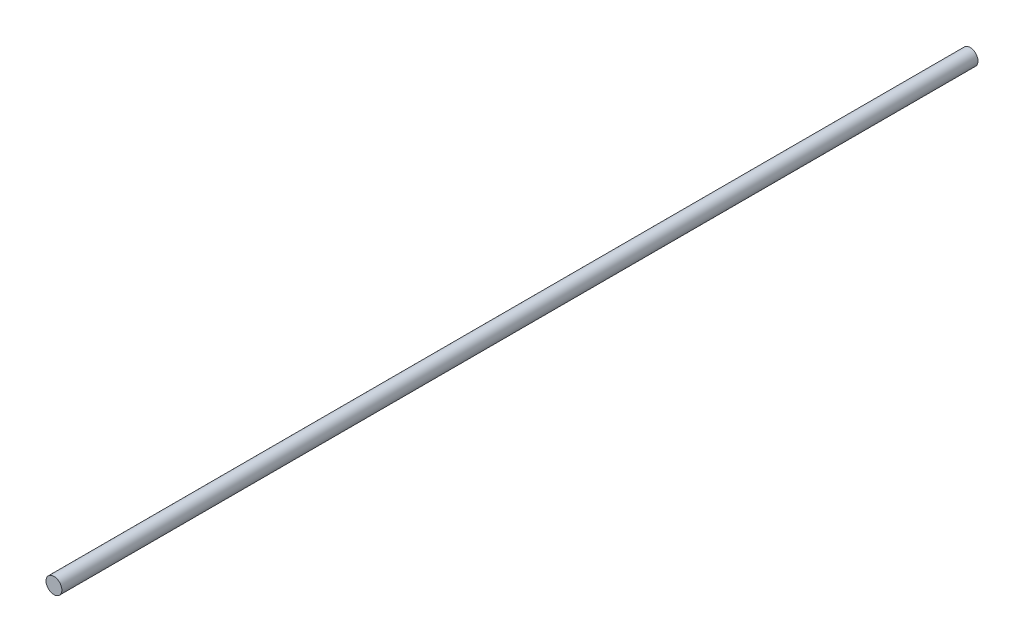
SolidWorks part; units mm, degrees
ref_plane "Front Plane" through (0, 0, 0) normal (0, 0, 1) x (1, 0, 0)
ref_plane "Top Plane" through (0, 0, 0) normal (0, 1, 0) x (1, 0, 0)
ref_plane "Right Plane" through (0, 0, 0) normal (1, 0, 0) x (0, 0, -1)
sketch "Sketch1" plane through (0, 0, 0) normal (0, 0, 1) x (1, 0, 0)
  circle A0 centre (0, 0) radius 4
extrude "Boss-Extrude2" add sketch "Sketch1" along normal mid plane 462.5
